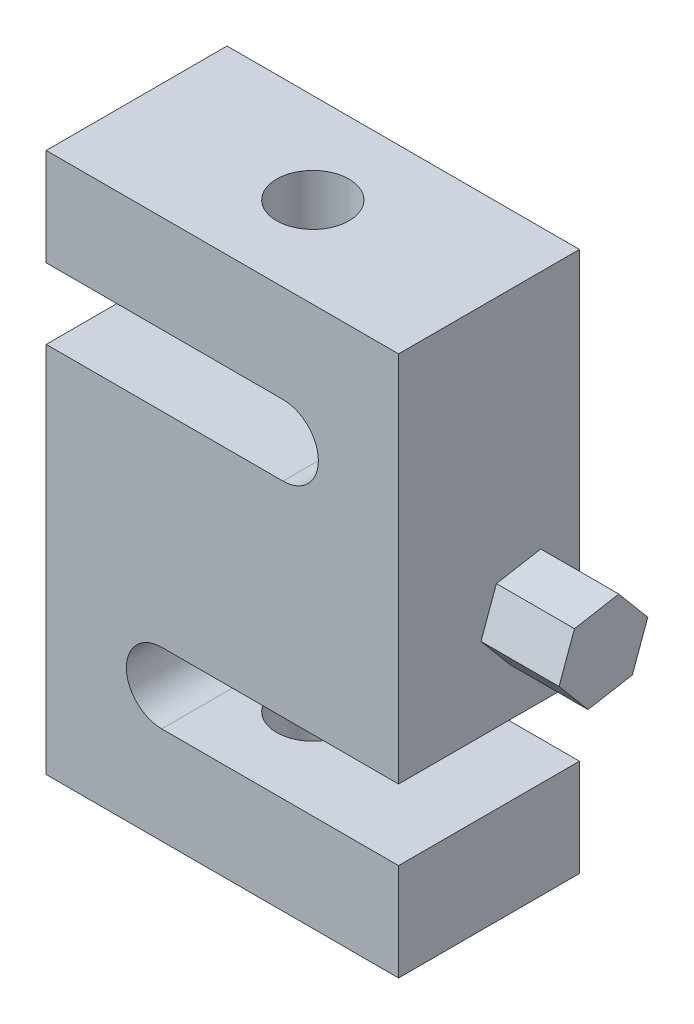
SolidWorks part; units mm, degrees
ref_plane "Front Plane" through (0, 0, 0) normal (0, 0, 1) x (1, 0, 0)
ref_plane "Top Plane" through (0, 0, 0) normal (0, 1, 0) x (1, 0, 0)
ref_plane "Right Plane" through (0, 0, 0) normal (1, 0, 0) x (0, 0, -1)
sketch "Sketch1" plane through (0, 0, 0) normal (0, 0, 1) x (1, 0, 0)
  line L1 (24.8285, -38.0873) -> (-24.8285, -38.0873)
  line L2 (24.8285, -38.0873) -> (24.8285, 38.0873)
  line L3 (24.8285, 38.0873) -> (-24.8285, 38.0873)
  line L4 (-24.8285, -38.0873) -> (-24.8285, 38.0873)
  line L5 (24.8285, -38.0873) -> (-24.8285, 38.0873) construction
  line L6 (24.8285, 38.0873) -> (-24.8285, -38.0873) construction
  line L7 (-24.8285, 24.3713) -> (8.5471, 24.3713)
  line L8 (-24.8285, 24.3713) -> (-24.8285, 14.4145)
  line L9 (-24.8285, 14.4145) -> (8.5471, 14.4145)
  line L11 (24.8285, -24.3713) -> (-8.5471, -24.3713)
  line L12 (24.8285, -24.3713) -> (24.8285, -14.4145)
  line L13 (24.8285, -14.4145) -> (-8.5471, -14.4145)
  arc A0 (-8.5471, -14.4145) -> (-8.5471, -24.3713) centre (-8.5471, -19.3929) ccw
  arc A1 (8.5471, 24.3713) -> (8.5471, 14.4145) centre (8.5471, 19.3929) cw
  point P0 (0, 0)
  dimension "D7" = 33.3756
  dimension "D1" = 76.1746
  dimension "D2" = 49.657
  dimension "D3" = 9.9568
  dimension "D4" = 9.9568
  dimension "D5" = 13.716
  dimension "D6" = 13.716
  dimension "D8" = 33.3756
extrude "Boss-Extrude1" add sketch "Sketch1" along normal blind 25.4889 contours L7 A1 L9 L4 L1 L2 L11 A0 L13 L3
sketch "Sketch2" plane through (24.8285, 0, 0) normal (1, 0, 0) x (0, 0, -1)
  line L0 (-25.4889, -14.4145) -> (0, -14.4145) construction
  line L1 (-11.7006, 3.1508) -> (-13.8738, -2.8157)
  line L2 (-13.8738, -2.8157) -> (-9.7932, -7.6811)
  line L3 (-9.7932, -7.6811) -> (-3.5394, -6.5798)
  line L4 (-3.5394, -6.5798) -> (-1.3662, -0.6133)
  line L5 (-1.3662, -0.6133) -> (-5.4468, 4.2521)
  line L6 (-5.4468, 4.2521) -> (-11.7006, 3.1508)
  line L7 (0, -14.4145) -> (0, 38.0873) construction
  circle A0 centre (-7.62, -1.7145) radius 5.4993 construction
  dimension "D1" = 12.7
  dimension "D2" = 6.35
  dimension "D3" = 7.62
extrude "Boss-Extrude2" add sketch "Sketch2" along normal blind 10.9982
sketch "Sketch3" plane through (0, 38.0873, 0) normal (0, 1, 0) x (1, 0, 0)
  line L0 (-24.8285, -12.7445) -> (24.8285, -12.7445) construction
  line L1 (0, 0) -> (0, -25.4889) construction
  line L4 (24.8285, 0) -> (-24.8285, 0)
  line L5 (-24.8285, 0) -> (-24.8285, -25.4889)
  line L6 (-24.8285, -25.4889) -> (24.8285, -25.4889)
  line L7 (24.8285, -25.4889) -> (24.8285, 0)
  line L8 (24.8285, 0) -> (-24.8285, 0)
  line L9 (-24.8285, 0) -> (-24.8285, -25.4889)
  line L10 (-24.8285, -25.4889) -> (24.8285, -25.4889)
  line L11 (24.8285, -25.4889) -> (24.8285, 0)
  circle A0 centre (0, -12.7445) radius 3.175
  point P9 (0, -12.7445)
  dimension "D2" = 6.35
  dimension "D1" = 0
hole_wizard "Tap Drill for M12x1.75 Tap1" positions "Sketch3" profile "Sketch4" hole size "M12x1.75" standard "ANSI Metric"
sketch "Sketch4" plane through (0, 38.0873, 12.7445) normal (1, 0, 0) x (0, 0, 1)
  line L0 (0, 0) -> (0, 22.1144)
  line L1 (0, 22.1144) -> (5.1, 19.05)
  line L2 (5.1, 19.05) -> (5.1, 0)
  line L5 (5.1, 0) -> (0, 0)
  line L10 (0, 22.1144) -> (-5.1, 19.05) construction
  line L11 (0, -6.35) -> (0, 107.95) construction
  dimension "Hole Dia." = 10.2
  dimension "Hole Depth" = 19.05
  dimension "Drill Angle" = 118
hole_wizard "Tap Drill for M12x1.75 Tap2" positions "Sketch5" profile "Sketch6" hole size "M12x1.75" standard "ANSI Metric"
sketch "Sketch5" plane through (0, -38.0873, 0) normal (0, -1, 0) x (-1, 0, 0)
  line L0 (-24.8285, -12.7445) -> (24.8285, -12.7445) construction
  line L1 (0, 0) -> (0, -25.4889) construction
  line L12 (-24.8285, -25.4889) -> (24.8285, -25.4889) construction
  line L13 (24.8285, -25.4889) -> (24.8285, 0) construction
  line L14 (-24.8285, -25.4889) -> (-24.8285, 0) construction
  circle A0 centre (0, -12.7445) radius 3.175
  point P9 (0, -12.7445)
  point P11 (0, 0)
  point P12 (0, 0)
  point P14 (0, 0)
  point P17 (0, 0)
  point P20 (-21.1363, -12.7445)
  dimension "D2" = 6.35
sketch "Sketch6" plane through (0, -38.0873, 12.7445) normal (1, 0, 0) x (0, 0, -1)
  line L0 (0, 0) -> (0, 22.1144)
  line L1 (0, 22.1144) -> (5.1, 19.05)
  line L2 (5.1, 19.05) -> (5.1, 0)
  line L5 (5.1, 0) -> (0, 0)
  line L10 (0, 22.1144) -> (-5.1, 19.05) construction
  line L11 (0, -6.35) -> (0, 107.95) construction
  dimension "Hole Dia." = 10.2
  dimension "Hole Depth" = 19.05
  dimension "Drill Angle" = 118
